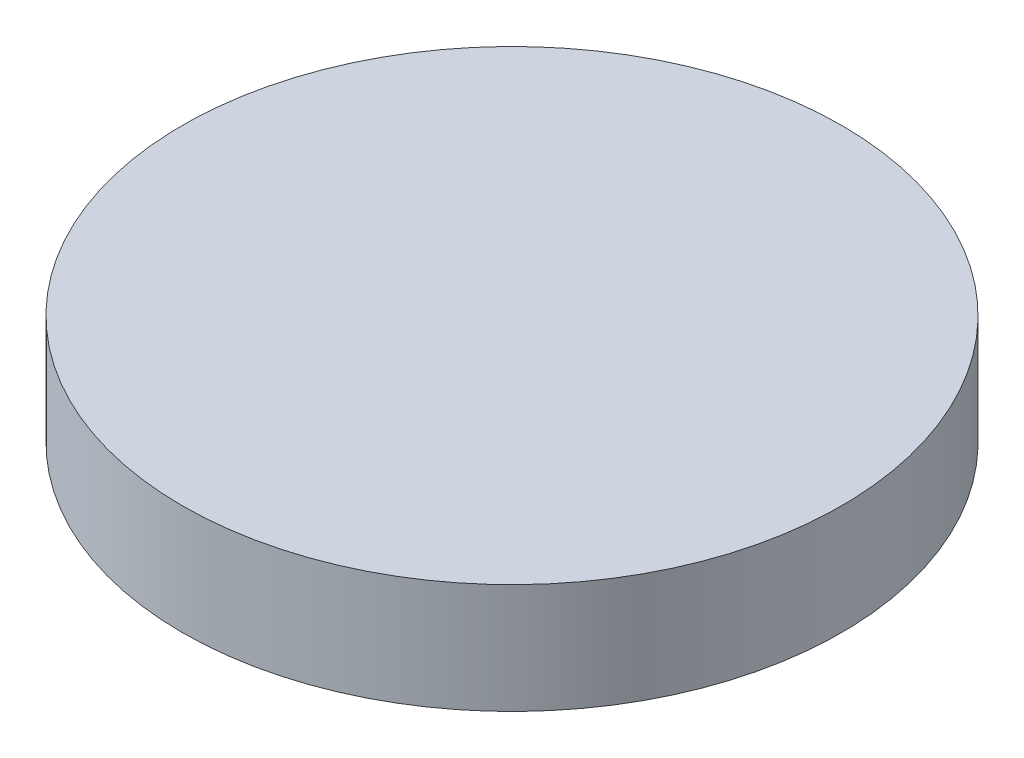
SolidWorks part; units mm, degrees
ref_plane "Front Plane" through (0, 0, 0) normal (0, 0, 1) x (1, 0, 0)
ref_plane "Top Plane" through (0, 0, 0) normal (0, 1, 0) x (1, 0, 0)
ref_plane "Right Plane" through (0, 0, 0) normal (1, 0, 0) x (0, 0, -1)
sketch "Sketch2" plane through (0, 0, 0) normal (0, 1, 0) x (1, 0, 0)
  circle A0 centre (0, 0) radius 4.7625
  dimension "D1" = 9.525
extrude "Boss-Extrude1" add sketch "Sketch2" along normal blind 1.5875
